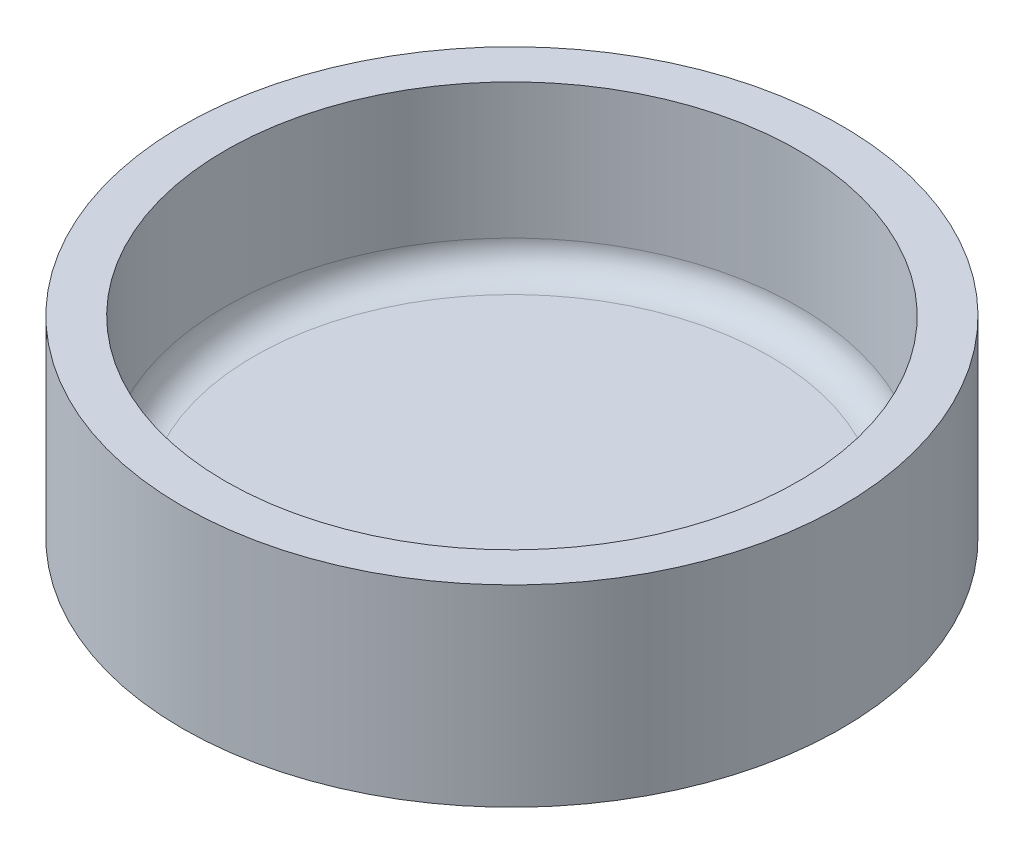
SolidWorks part; units mm, degrees
ref_plane "Front Plane" through (0, 0, 0) normal (0, 0, 1) x (1, 0, 0)
ref_plane "Top Plane" through (0, 0, 0) normal (0, 1, 0) x (1, 0, 0)
ref_plane "Right Plane" through (0, 0, 0) normal (1, 0, 0) x (0, 0, -1)
sketch "Sketch1" plane through (0, 0, 0) normal (0, 1, 0) x (1, 0, 0)
  circle A0 centre (0, 0) radius 57.5
  dimension "D1" = 115
extrude "Boss-Extrude1" add sketch "Sketch1" along normal blind 33.6
sketch "Sketch2" plane through (0, 33.6, 0) normal (0, 1, 0) x (1, 0, 0)
  circle A0 centre (0, 0) radius 50
  dimension "D1" = 100
extrude "Cut-Extrude1" cut sketch "Sketch2" against normal blind 28.6
fillet "Fillet1" radius 5 1 edges at (0, 5, 50)
